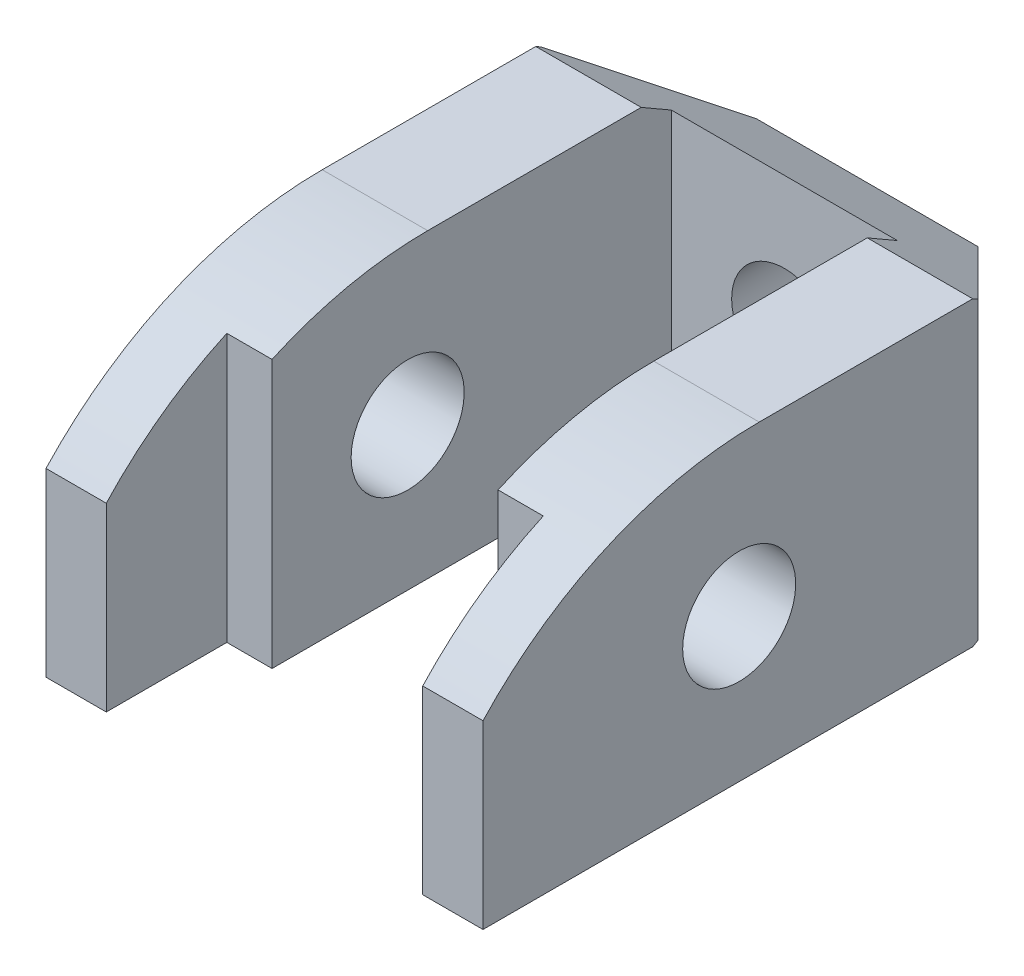
SolidWorks part; units mm, degrees
material "1060 Alloy"
ref_plane "Front Plane" through (0, 0, 0) normal (0, 0, 1) x (1, 0, 0)
ref_plane "Top Plane" through (0, 0, 0) normal (0, 1, 0) x (1, 0, 0)
ref_plane "Right Plane" through (0, 0, 0) normal (1, 0, 0) x (0, 0, -1)
sketch "Sketch1" plane through (0, 0, 0) normal (1, 0, 0) x (0, 0, -1)
  line L0 (0, 0) -> (65, 0)
  line L1 (0, 0) -> (0, 24)
  line L2 (65, 0) -> (80, 8.6603)
  line L3 (80, 8.6603) -> (80, 31.3397)
  line L4 (80, 31.3397) -> (65, 40)
  line L5 (65, 40) -> (36.6606, 40)
  arc A0 (36.6606, 40) -> (0, 24) centre (36.6606, -10) ccw
  circle A1 centre (34, 19) radius 7.5
  dimension "D7" = 50
  dimension "D9" = 15
  dimension "D1" = 65
  dimension "D2" = 24
  dimension "D3" = 15
  dimension "D4" = 30
  dimension "D5" = 15
  dimension "D6" = 30
  dimension "D8" = 40
  dimension "D10" = 19
  dimension "D11" = 31
extrude "Boss-Extrude1" add sketch "Sketch1" along normal blind 58
sketch "Sketch3" plane through (0, 0, 0) normal (0, 1, 0) x (1, 0, 0)
  line L0 (29, 80.0246) -> (29, 0.0246) construction
  line L3 (58, 0) -> (0, 0) construction
  line L4 (0, 36.6606) -> (0, 0) construction
  line L5 (58, 0) -> (58, 36.6606) construction
  line L6 (58, 65) -> (58, 36.6606) construction
  line L7 (58, 36.6606) -> (0, 36.6606) construction
  line L8 (0, 65) -> (0, 36.6606) construction
  line L9 (58, 65) -> (0, 65) construction
  line L10 (0, 80) -> (0, 65) construction
  line L11 (58, 80) -> (0, 80) construction
  line L12 (58, 0) -> (0, 0)
  line L13 (0, 36.6606) -> (0, 0)
  line L14 (58, 0) -> (58, 36.6606)
  line L15 (58, 65) -> (58, 36.6606)
  line L16 (58, 36.6606) -> (0, 36.6606)
  line L17 (0, 65) -> (0, 36.6606)
  line L18 (58, 65) -> (0, 65)
  line L19 (0, 80) -> (0, 65)
  line L20 (58, 80) -> (0, 80)
  line L22 (14, 69) -> (44, 69)
  line L23 (14, 69) -> (14, 16)
  line L24 (14, 16) -> (44, 16)
  line L25 (44, 69) -> (44, 16)
  line L26 (14, 69) -> (44, 16) construction
  line L27 (14, 16) -> (44, 69) construction
  point P4 (29, 42.5)
  dimension "D1" = 11
  dimension "D2" = 16
  dimension "D3" = 16
  dimension "D4" = 14
  dimension "D5" = 14
extrude "Cut-Extrude1" cut sketch "Sketch3" against normal blind 10 and the other way through all contours L25 L24 L23 L22
sketch "Sketch5" plane through (0, 0, 0) normal (0, 1, 0) x (1, 0, 0)
  line L0 (29, 80) -> (29, 0) construction
  line L1 (58, 80) -> (0, 80) construction
  line L2 (58, 0) -> (0, 0) construction
  line L3 (58, 65) -> (58, 36.6606) construction
  line L5 (44, 36.6606) -> (44, 16) construction
  line L6 (44, 65) -> (44, 36.6606) construction
  line L7 (58, 36.6606) -> (44, 36.6606) construction
  line L9 (14, 16) -> (14, 36.6606) construction
  line L10 (0, 36.6606) -> (0, 0) construction
  line L11 (14, 36.6606) -> (0, 36.6606) construction
  line L12 (0, 65) -> (0, 36.6606) construction
  line L13 (14, 65) -> (14, 36.6606) construction
  line L14 (14, 69) -> (14, 65) construction
  line L15 (44, 69) -> (44, 65) construction
  line L16 (58, 65) -> (44, 65) construction
  line L17 (58, 80) -> (58, 65) construction
  line L18 (0, 80) -> (0, 65) construction
  line L19 (14, 65) -> (0, 65) construction
  line L20 (14, 69) -> (44, 69) construction
  line L21 (58, 65) -> (58, 36.6606)
  line L22 (58, 16) -> (58, 0)
  line L23 (44, 36.6606) -> (44, 16)
  line L24 (44, 65) -> (44, 36.6606)
  line L25 (58, 36.6606) -> (44, 36.6606)
  line L26 (8, 16) -> (44, 16)
  line L27 (14, 16) -> (14, 36.6606)
  line L28 (0, 36.6606) -> (0, 0)
  line L29 (50, 16) -> (58, 16)
  line L30 (14, 36.6606) -> (0, 36.6606)
  line L31 (0, 65) -> (0, 36.6606)
  line L32 (14, 65) -> (14, 36.6606)
  line L33 (14, 69) -> (14, 65)
  line L34 (44, 69) -> (44, 65)
  line L35 (58, 65) -> (44, 65)
  line L36 (58, 80) -> (58, 65)
  line L37 (0, 80) -> (0, 65)
  line L38 (14, 65) -> (0, 65)
  line L39 (14, 69) -> (44, 69)
  line L40 (58, 80) -> (0, 80)
  line L41 (58, 0) -> (50, 0)
  line L42 (50, 0) -> (50, 16)
  line L43 (50, 16) -> (44, 16)
  line L44 (50, 0) -> (58, 0)
  line L45 (58, 16) -> (58, 0)
  line L46 (0, 16) -> (0, 0)
  line L47 (0, 0) -> (8, 0)
  line L48 (8, 0) -> (8, 16)
  line L49 (8, 16) -> (0, 16)
  line L50 (8, 0) -> (50, 0)
  dimension "D1" = 8
  dimension "D2" = 6
  dimension "D3" = 16
extrude "Cut-Extrude3" cut sketch "Sketch5" against normal through all and the other way up to next contours L0 L26 L48 L50 | L26 L0 L50 L42 L43
sketch "Sketch7" plane through (0, 0, 0) normal (0, 1, 0) x (1, 0, 0)
  line L0 (29, 80) -> (29, 69) construction
  line L1 (0, 65) -> (0, 36.6606) construction
  line L2 (58, 80) -> (0, 80) construction
  line L3 (14, 69) -> (44, 69) construction
  line L4 (0, 65.6967) -> (14.3033, 80)
  line L5 (0, 80) -> (0, 65) construction
  line L6 (14.3033, 80) -> (0, 80)
  line L7 (0, 80) -> (0, 65.6967)
  line L8 (58, 65.6967) -> (43.6967, 80)
  line L9 (43.6967, 80) -> (58, 80)
  line L10 (58, 80) -> (58, 65.6967)
  dimension "D1" = 45
  dimension "D2" = 14.3033
extrude "Cut-Extrude4" cut sketch "Sketch7" along normal through all contours L7 L4 L6 | L8 L9 L10
sketch "Sketch8" plane through (0, 0, -80) normal (0, 0, -1) x (-1, 0, 0)
  line L0 (-29, 31.3397) -> (-29, 8.6603) construction
  line L1 (-43.6967, 31.3397) -> (-14.3033, 31.3397) construction
  line L2 (-43.6967, 8.6603) -> (-14.3033, 8.6603) construction
  circle A1 centre (-29, 20) radius 7
  dimension "D1" = 14
extrude "Cut-Extrude5" cut sketch "Sketch8" against normal through all
equation "\"A\"= 58.00mm"
equation "\"B\"= 40.00mm"
equation "\"C\"= 65.00mm"
equation "\"D1@Sketch1\"=\"C\""
equation "\"D8@Sketch1\"=\"B\""
